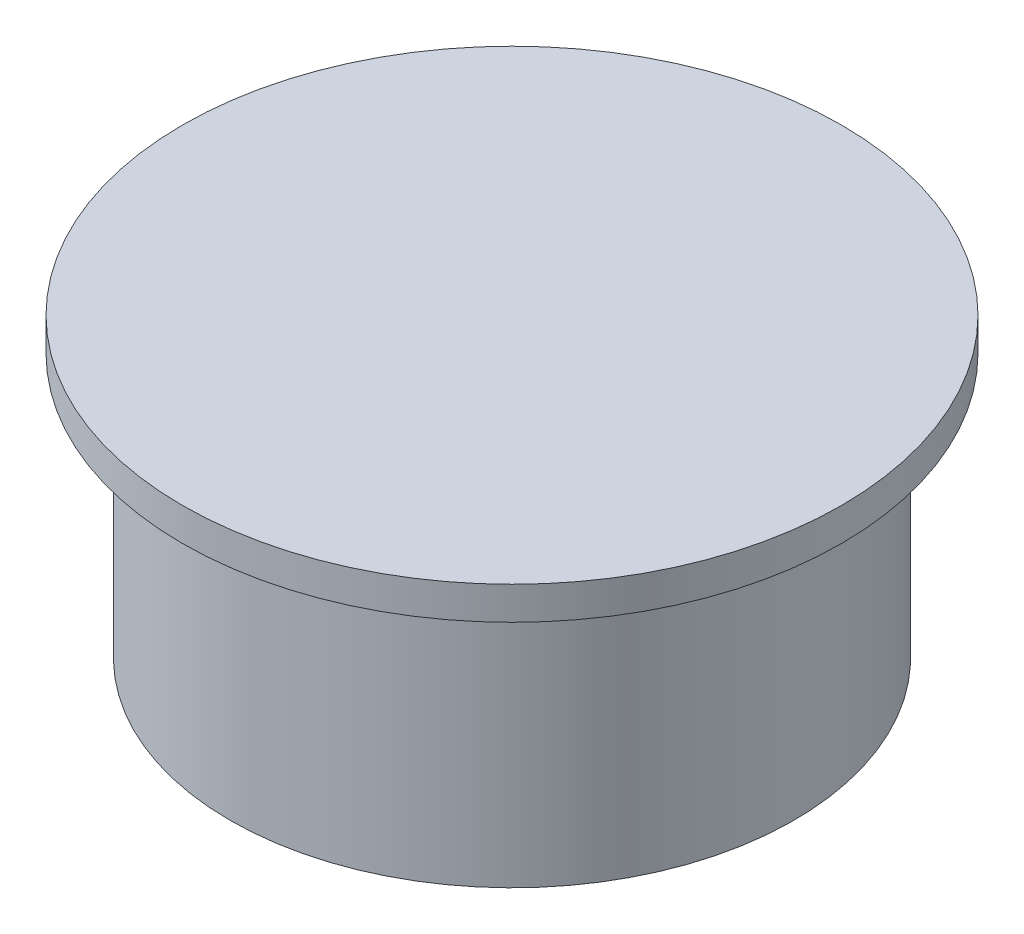
SolidWorks part; units mm, degrees
ref_plane "Front Plane" through (0, 0, 0) normal (0, 0, 1) x (1, 0, 0)
ref_plane "Top Plane" through (0, 0, 0) normal (0, 1, 0) x (1, 0, 0)
ref_plane "Right Plane" through (0, 0, 0) normal (1, 0, 0) x (0, 0, -1)
sketch "Sketch1" plane through (0, 0, 0) normal (0, 1, 0) x (1, 0, 0)
  line L0 (-60, 70) -> (60, 70)
  line L1 (-60, 70) -> (-60, -50)
  line L2 (-60, -50) -> (60, -50)
  line L3 (60, 70) -> (60, -50)
  line L4 (-45, -50) -> (45, -50)
  line L5 (45, -50) -> (45, 50)
  line L6 (45, 50) -> (-45, 50)
  line L7 (-45, 50) -> (-45, -50)
  line L8 (-45, 0) -> (45, 0) construction
  line L9 (-13, 13) -> (13, 13)
  line L10 (-13, 13) -> (-13, -13)
  line L11 (-13, -13) -> (13, -13)
  line L12 (13, 13) -> (13, -13)
  line L13 (0, 13) -> (0, -13) construction
  line L14 (13, 0) -> (-13, 0) construction
  circle A0 centre (0, 0) radius 18.3848 construction
  circle A1 centre (0, 0) radius 21.3848
  circle A2 centre (0, 0) radius 21.5848
  circle A3 centre (0, 0) radius 24.5848
sketch "Sketch2" plane through (0, 0, 0) normal (0, 1, 0) x (1, 0, 0)
  line L0 (-13, 13) -> (13, 13) construction
  line L1 (13, 13) -> (13, -13) construction
  line L2 (-13, -13) -> (13, -13) construction
  line L3 (-13, 13) -> (-13, -13) construction
  line L4 (-13, 13) -> (13, 13)
  line L5 (13, 13) -> (13, -13)
  line L6 (-13, -13) -> (13, -13)
  line L7 (-13, 13) -> (-13, -13)
  circle A0 centre (0, 0) radius 21.3848 construction
  circle A1 centre (0, 0) radius 21.3848
extrude "Boss-Extrude1" add sketch "Sketch2" along normal mid plane 20
sketch "Sketch4" plane through (0, 10, 0) normal (0, 1, 0) x (1, 0, 0)
  circle A0 centre (0, 0) radius 25
  dimension "D1" = 50
extrude "Boss-Extrude2" add sketch "Sketch4" along normal blind 2.5
fillet "Fillet1" radius 2 1 edges at (0, 10, 21.3848)
